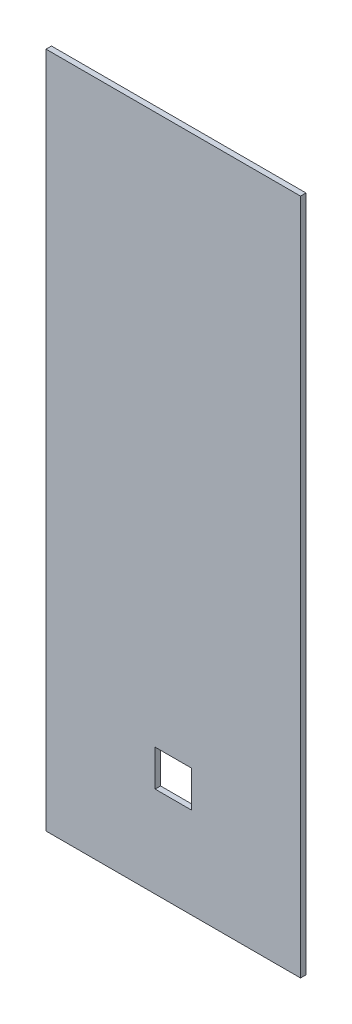
SolidWorks part; units mm, degrees
material "Acrylic (Medium-high impact)"
ref_plane "Front Plane" through (0, 0, 0) normal (0, 0, 1) x (1, 0, 0)
ref_plane "Top Plane" through (0, 0, 0) normal (0, 1, 0) x (1, 0, 0)
ref_plane "Right Plane" through (0, 0, 0) normal (1, 0, 0) x (0, 0, -1)
sketch "Sketch1" plane through (0, 0, 0) normal (0, 0, 1) x (1, 0, 0)
  line L1 (140, -372.5) -> (-140, -372.5)
  line L2 (140, -372.5) -> (140, 372.5)
  line L3 (140, 372.5) -> (-140, 372.5)
  line L4 (-140, -372.5) -> (-140, 372.5)
  line L5 (140, -372.5) -> (-140, 372.5) construction
  line L6 (140, 372.5) -> (-140, -372.5) construction
  point P0 (0, 0)
  dimension "D1" = 280
  dimension "D2" = 745
extrude "Boss-Extrude1" add sketch "Sketch1" along normal blind 6
sketch "Sketch2" plane through (0, 0, 6) normal (0, 0, 1) x (1, 0, 0)
  line L0 (0, 372.5) -> (0, 0) construction
  line L1 (140, 372.5) -> (-140, 372.5) construction
  line L2 (-140, -252.5) -> (140, -252.5) construction
  line L3 (-140, 372.5) -> (-140, -372.5) construction
  line L4 (140, -372.5) -> (140, 372.5) construction
  line L6 (20, -272.5) -> (-20, -272.5)
  line L7 (20, -272.5) -> (20, -232.5)
  line L8 (20, -232.5) -> (-20, -232.5)
  line L9 (-20, -272.5) -> (-20, -232.5)
  line L10 (20, -272.5) -> (-20, -232.5) construction
  line L11 (20, -232.5) -> (-20, -272.5) construction
  point P11 (0, -252.5)
  dimension "D1" = 625
  dimension "D2" = 40
  dimension "D3" = 40
extrude "Cut-Extrude1" cut sketch "Sketch2" against normal through all
